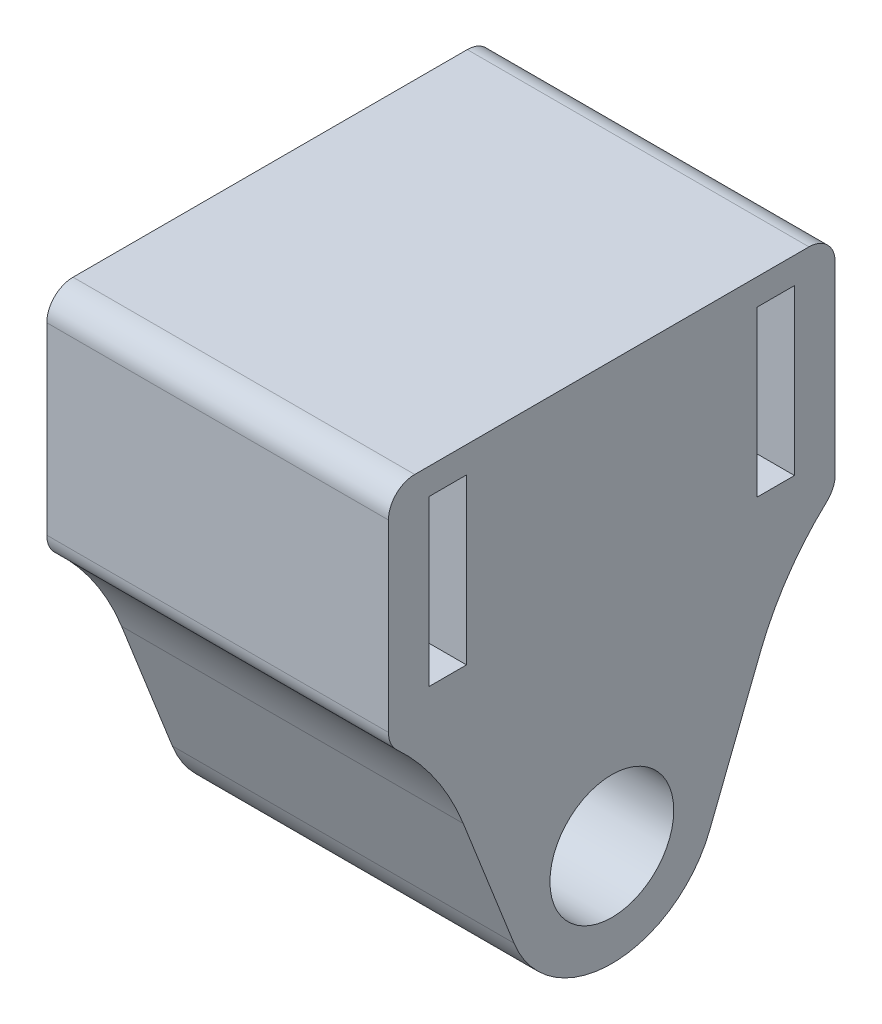
SolidWorks part; units mm, degrees
material "BUTYL"
ref_plane "Front Plane" through (0, 0, 0) normal (0, 0, 1) x (1, 0, 0)
ref_plane "Top Plane" through (0, 0, 0) normal (0, 1, 0) x (1, 0, 0)
ref_plane "Right Plane" through (0, 0, 0) normal (1, 0, 0) x (0, 0, -1)
sketch "Sketch1" plane through (0, 0, 0) normal (1, 0, 0) x (0, 0, -1)
  line L0 (0, 7.935) -> (0, -7.935) construction
  line L1 (-8.5, 7.935) -> (8.5, 7.935)
  line L2 (8.5, 7.935) -> (8.5, -1.065)
  line L3 (-8.5, 7.935) -> (-8.5, -1.065)
  line L4 (9.565, -11.935) -> (-10.8746, -11.935) construction
  line L5 (-3.7225, -9.399) -> (-7, -1.065)
  line L6 (-7, -1.065) -> (-8.5, -1.065)
  line L7 (3.7225, -9.399) -> (7, -1.065)
  line L8 (7, -1.065) -> (8.5, -1.065)
  line L9 (-7, -1.065) -> (7, -1.065) construction
  circle A0 centre (0, -7.935) radius 4 construction
  arc A1 (-3.7225, -9.399) -> (3.7225, -9.399) centre (0, -7.935) ccw
  point P3 (0, 0)
  point P6 (0, 7.935)
  point P12 (0, -1.065)
  dimension "D4" = 8
  dimension "D1" = 19.87
  dimension "D2" = 17
  dimension "D3" = 9
  dimension "D5" = 14
extrude "Boss-Extrude1" add sketch "Sketch1" against normal blind 13
fillet "Fillet1" radius 1 4 edges at (-6.5, -1.065, -8.5) (-6.5, -1.065, 8.5) (-6.5, 7.935, -8.5) (-6.5, 7.935, 8.5)
fillet "Fillet2" radius 10 2 edges at (-6.5, -1.065, -7) (-6.5, -1.065, 7)
sketch "Sketch4" plane through (-13, 0, 0) normal (-1, 0, 0) x (0, 0, 1)
  line L0 (0, 0) -> (0, 3.805) construction
  line L1 (-5.53, 3.805) -> (5.53, 3.805) construction
  line L2 (-7.5, 7.935) -> (7.5, 7.935) construction
  line L3 (5.53, 0.675) -> (6.95, 0.675)
  line L4 (5.53, 0.675) -> (5.53, 6.935)
  line L5 (5.53, 6.935) -> (6.95, 6.935)
  line L6 (6.95, 0.675) -> (6.95, 6.935)
  line L7 (5.53, 0.675) -> (6.95, 6.935) construction
  line L8 (5.53, 6.935) -> (6.95, 0.675) construction
  line L9 (-9.2011, -10.415) -> (10.1941, -10.415) construction
  line L10 (-6.95, 6.935) -> (-5.53, 6.935)
  line L11 (-6.95, 6.935) -> (-6.95, 0.675)
  line L12 (-6.95, 0.675) -> (-5.53, 0.675)
  line L13 (-5.53, 6.935) -> (-5.53, 0.675)
  line L14 (-6.95, 6.935) -> (-5.53, 0.675) construction
  line L15 (-6.95, 0.675) -> (-5.53, 6.935) construction
  line L16 (0, -8.06) -> (0, 0) construction
  circle A0 centre (0, -8.06) radius 2.355
  point P9 (0, 3.805)
  point P10 (6.24, 3.805)
  point P11 (5.53, 3.805)
  point P14 (-6.24, 3.805)
  point P19 (-5.53, 3.805)
  dimension "D5" = 4.71
  dimension "D6" = 17.35
  dimension "D1" = 6.26
  dimension "D2" = 1.42
  dimension "D3" = 11.06
  dimension "D4" = 1
extrude "Cut-Extrude1" cut sketch "Sketch4" against normal blind 18
